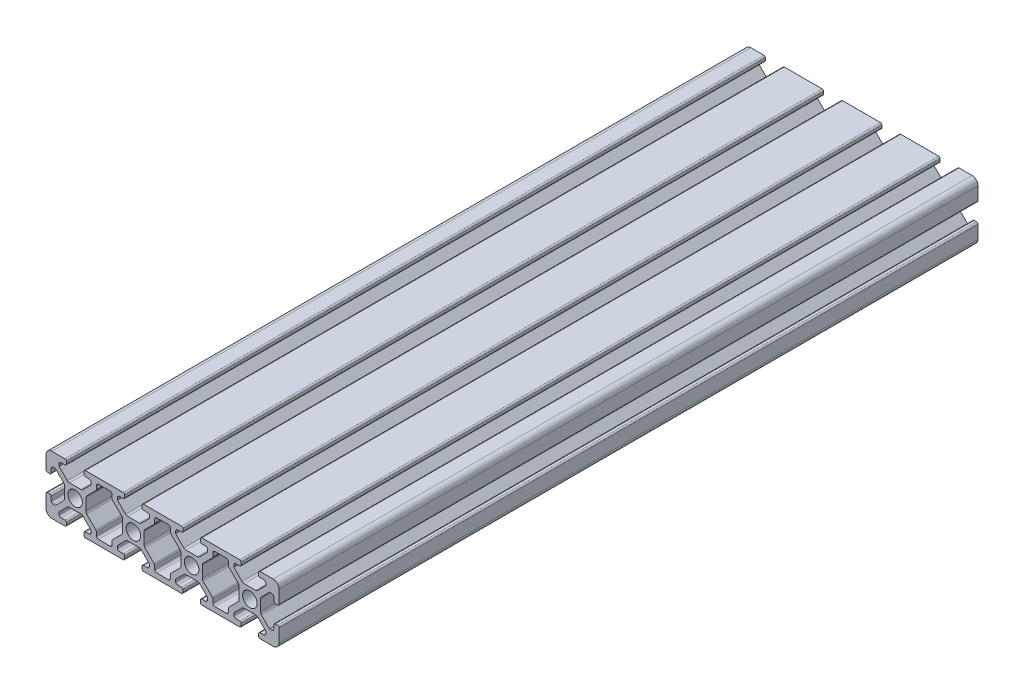
SolidWorks part; units mm, degrees
material "6063-T5"
ref_plane "Front Plane" through (0, 0, 0) normal (0, 0, 1) x (1, 0, 0)
ref_plane "Top Plane" through (0, 0, 0) normal (0, 1, 0) x (1, 0, 0)
ref_plane "Right Plane" through (0, 0, 0) normal (1, 0, 0) x (0, 0, -1)
sketch "Sketch1" plane through (0, 0, 0) normal (0, 0, 1) x (1, 0, 0)
  line L0 (2, 0) -> (6.5, 0)
  line L1 (80, 2) -> (80, 6.5)
  line L2 (78, 20) -> (73.5, 20)
  line L3 (0, 18) -> (0, 13.5)
  line L4 (33, 19.5) -> (33, 18.7)
  line L5 (27, 19.5) -> (27, 18.7)
  line L6 (7, 19.5) -> (7, 18.7)
  line L7 (13, 19.5) -> (13, 18.7)
  line L8 (6.5, 20) -> (2, 20)
  line L9 (53, 19.5) -> (53, 18.7)
  line L10 (47, 19.5) -> (47, 18.7)
  line L11 (73, 19.5) -> (73, 18.7)
  line L12 (67, 19.5) -> (67, 18.7)
  line L13 (33, 1.3) -> (33, 0.5)
  line L14 (27, 1.3) -> (27, 0.5)
  line L15 (53, 1.3) -> (53, 0.5)
  line L16 (47, 1.3) -> (47, 0.5)
  line L17 (73, 1.3) -> (73, 0.5)
  line L18 (67, 1.3) -> (67, 0.5)
  line L19 (13, 1.3) -> (13, 0.5)
  line L20 (7, 1.3) -> (7, 0.5)
  line L21 (13.5, 20) -> (26.5, 20) construction
  line L22 (26.5, 20) -> (13.5, 20)
  line L23 (46.5, 20) -> (33.5, 20)
  line L24 (66.5, 20) -> (53.5, 20)
  line L25 (73.5, 0) -> (78, 0)
  line L26 (53.5, 0) -> (66.5, 0)
  line L27 (33.5, 0) -> (46.5, 0)
  line L28 (13.5, 0) -> (26.5, 0)
  line L29 (79.5, 13) -> (78.7, 13)
  line L30 (79.5, 7) -> (78.7, 7)
  line L31 (0.5, 13) -> (1.3, 13)
  line L32 (0.5, 7) -> (1.3, 7)
  line L33 (0, 6.5) -> (0, 2)
  line L34 (80, 13.5) -> (80, 18)
  line L35 (1.8, 13.5) -> (1.8, 14.75)
  line L36 (5.25, 18.2) -> (6.5, 18.2)
  line L37 (78.2, 14.75) -> (78.2, 13.5)
  line L38 (74.75, 1.8) -> (73.5, 1.8)
  line L39 (1.8, 5.25) -> (1.8, 6.5)
  line L40 (13.5, 18.2) -> (14.75, 18.2)
  line L41 (6.5, 1.8) -> (5.25, 1.8)
  line L42 (33.5, 18.2) -> (34.75, 18.2)
  line L43 (26.5, 1.8) -> (25.25, 1.8)
  line L44 (53.5, 18.2) -> (54.75, 18.2)
  line L45 (46.5, 1.8) -> (45.25, 1.8)
  line L46 (73.5, 18.2) -> (74.75, 18.2)
  line L47 (66.5, 1.8) -> (65.25, 1.8)
  line L48 (78.2, 6.5) -> (78.2, 5.25)
  line L49 (12.6701, 13.9429) -> (15.5, 16.7728)
  line L50 (12.6701, 6.0571) -> (15.5, 3.2272)
  line L51 (32.6701, 13.9429) -> (35.5, 16.7728)
  line L52 (33.9429, 12.6701) -> (37.0803, 15.8075)
  line L53 (27.3299, 13.9429) -> (24.5, 16.7728)
  line L54 (22.9197, 15.8075) -> (26.0571, 12.6701)
  line L55 (27.3299, 6.0571) -> (24.5, 3.2272)
  line L56 (22.9197, 4.1925) -> (26.0571, 7.3299)
  line L57 (47.3299, 13.9429) -> (44.5, 16.7728)
  line L58 (42.9197, 15.8075) -> (46.0571, 12.6701)
  line L59 (47.3299, 6.0571) -> (44.5, 3.2272)
  line L60 (42.9197, 4.1925) -> (46.0571, 7.3299)
  line L61 (67.3299, 13.9429) -> (64.5, 16.7728)
  line L62 (62.9197, 15.8075) -> (66.0571, 12.6701)
  line L63 (67.3299, 6.0571) -> (64.5, 3.2272)
  line L64 (62.9197, 4.1925) -> (66.0571, 7.3299)
  line L65 (33.9429, 7.3299) -> (37.0803, 4.1925)
  line L66 (13.9429, 12.6701) -> (17.0803, 15.8075)
  line L67 (6.0571, 7.3299) -> (3.2272, 4.5)
  line L68 (7.3299, 6.0571) -> (4.5, 3.2272)
  line L69 (7.3299, 13.9429) -> (4.5, 16.7728)
  line L70 (32.6701, 6.0571) -> (35.5, 3.2272)
  line L71 (13.9429, 7.3299) -> (17.0803, 4.1925)
  line L72 (52.6701, 13.9429) -> (55.5, 16.7728)
  line L73 (6.0571, 12.6701) -> (3.2272, 15.5)
  line L74 (53.9429, 12.6701) -> (57.0803, 15.8075)
  line L75 (53.9429, 7.3299) -> (57.0803, 4.1925)
  line L76 (52.6701, 6.0571) -> (55.5, 3.2272)
  line L77 (72.6701, 13.9429) -> (75.5, 16.7728)
  line L78 (73.9429, 12.6701) -> (76.7728, 15.5)
  line L79 (73.9429, 7.3299) -> (76.7728, 4.5)
  line L80 (72.6701, 6.0571) -> (75.5, 3.2272)
  line L81 (28.037, 13.65) -> (31.963, 13.65)
  line L82 (18.05, 18.2) -> (21.95, 18.2)
  line L83 (14.75, 1.8) -> (13.5, 1.8)
  line L84 (15.5, 17.45) -> (15.5, 16.7728)
  line L85 (34.75, 1.8) -> (33.5, 1.8)
  line L86 (4.5, 17.45) -> (4.5, 16.7728)
  line L87 (54.75, 1.8) -> (53.5, 1.8)
  line L88 (24.5, 17.45) -> (24.5, 16.7728)
  line L89 (27.7144, 8.9872) -> (21.8, 3.0728) [skipped]
  line L90 (25.25, 18.2) -> (26.5, 18.2)
  line L91 (27.7144, 11.0128) -> (21.8, 16.9272) [skipped]
  line L92 (45.25, 18.2) -> (46.5, 18.2)
  line L93 (33.65, 11.963) -> (33.65, 8.037)
  line L94 (31.963, 6.35) -> (28.037, 6.35)
  line L95 (26.35, 8.037) -> (26.35, 11.963)
  line L96 (65.25, 18.2) -> (66.5, 18.2)
  line L97 (44.5, 17.45) -> (44.5, 16.7728)
  line L98 (35.5, 17.45) -> (35.5, 16.7728)
  line L99 (47.7144, 8.9872) -> (41.8, 3.0728) [skipped]
  line L100 (47.7144, 11.0128) -> (41.8, 16.9272) [skipped]
  line L101 (67.7144, 11.0128) -> (61.8, 16.9272) [skipped]
  line L102 (67.7144, 8.9872) -> (61.8, 3.0728) [skipped]
  line L103 (13.65, 11.963) -> (13.65, 8.037)
  line L104 (11.963, 6.35) -> (8.037, 6.35)
  line L105 (6.35, 8.037) -> (6.35, 11.963)
  line L106 (8.037, 13.65) -> (11.963, 13.65)
  line L107 (48.037, 13.65) -> (51.963, 13.65)
  line L108 (53.65, 11.963) -> (53.65, 8.037)
  line L109 (51.963, 6.35) -> (48.037, 6.35)
  line L110 (46.35, 8.037) -> (46.35, 11.963)
  line L111 (68.037, 13.65) -> (71.963, 13.65)
  line L112 (73.65, 11.963) -> (73.65, 8.037)
  line L113 (71.963, 6.35) -> (68.037, 6.35)
  line L114 (66.35, 8.037) -> (66.35, 11.963)
  line L115 (64.5, 17.45) -> (64.5, 16.7728)
  line L116 (55.5, 17.45) -> (55.5, 16.7728)
  line L117 (4.5, 2.55) -> (4.5, 3.2272)
  line L118 (75.5, 17.45) -> (75.5, 16.7728)
  line L119 (24.5, 2.55) -> (24.5, 3.2272)
  line L120 (15.5, 2.55) -> (15.5, 3.2272)
  line L121 (44.5, 2.55) -> (44.5, 3.2272)
  line L122 (35.5, 2.55) -> (35.5, 3.2272)
  line L123 (64.5, 2.55) -> (64.5, 3.2272)
  line L124 (55.5, 2.55) -> (55.5, 3.2272)
  line L125 (2.55, 15.5) -> (3.2272, 15.5)
  line L126 (75.5, 2.55) -> (75.5, 3.2272)
  line L127 (2.55, 4.5) -> (3.2272, 4.5)
  line L128 (77.45, 15.5) -> (76.7728, 15.5)
  line L129 (17.3, 17.45) -> (17.3, 16.3379)
  line L130 (77.45, 4.5) -> (76.7728, 4.5)
  line L131 (22.7, 17.45) -> (22.7, 16.3379)
  line L132 (38.05, 18.2) -> (41.95, 18.2)
  line L133 (37.3, 17.45) -> (37.3, 16.3379)
  line L134 (42.7, 17.45) -> (42.7, 16.3379)
  line L135 (58.05, 18.2) -> (61.95, 18.2)
  line L136 (57.3, 17.45) -> (57.3, 16.3379)
  line L137 (62.7, 17.45) -> (62.7, 16.3379)
  line L138 (17.3, 3.6621) -> (17.3, 2.55)
  line L139 (18.05, 1.8) -> (21.95, 1.8)
  line L140 (22.7, 2.55) -> (22.7, 3.6621)
  line L141 (37.3, 3.6621) -> (37.3, 2.55)
  line L142 (38.05, 1.8) -> (41.95, 1.8)
  line L143 (42.7, 2.55) -> (42.7, 3.6621)
  line L144 (57.3, 3.6621) -> (57.3, 2.55)
  line L145 (58.05, 1.8) -> (61.95, 1.8)
  line L146 (62.7, 2.55) -> (62.7, 3.6621)
  circle A0 centre (10, 10) radius 2.5
  circle A1 centre (30, 10) radius 2.5
  circle A2 centre (50, 10) radius 2.5
  circle A3 centre (70, 10) radius 2.5
  arc A4 (78, 0) -> (80, 2) centre (78, 2) ccw
  arc A5 (80, 18) -> (78, 20) centre (78, 18) ccw
  arc A6 (2, 0) -> (0, 2) centre (2, 2) cw
  arc A7 (2, 20) -> (0, 18) centre (2, 18) ccw
  arc A8 (12.6701, 13.9429) -> (11.963, 13.65) centre (11.963, 14.65) cw
  arc A9 (7.3299, 13.9429) -> (8.037, 13.65) centre (8.037, 14.65) ccw
  arc A10 (6.0571, 12.6701) -> (6.35, 11.963) centre (5.35, 11.963) cw
  arc A11 (6.0571, 7.3299) -> (6.35, 8.037) centre (5.35, 8.037) ccw
  arc A12 (7.3299, 6.0571) -> (8.037, 6.35) centre (8.037, 5.35) cw
  arc A13 (12.6701, 6.0571) -> (11.963, 6.35) centre (11.963, 5.35) ccw
  arc A14 (32.6701, 6.0571) -> (31.963, 6.35) centre (31.963, 5.35) ccw
  arc A15 (27.3299, 6.0571) -> (28.037, 6.35) centre (28.037, 5.35) cw
  arc A16 (27.3299, 13.9429) -> (28.037, 13.65) centre (28.037, 14.65) ccw
  arc A17 (32.6701, 13.9429) -> (31.963, 13.65) centre (31.963, 14.65) cw
  arc A18 (47.3299, 6.0571) -> (48.037, 6.35) centre (48.037, 5.35) cw
  arc A19 (52.6701, 6.0571) -> (51.963, 6.35) centre (51.963, 5.35) ccw
  arc A20 (52.6701, 13.9429) -> (51.963, 13.65) centre (51.963, 14.65) cw
  arc A21 (47.3299, 13.9429) -> (48.037, 13.65) centre (48.037, 14.65) ccw
  arc A22 (72.6701, 13.9429) -> (71.963, 13.65) centre (71.963, 14.65) cw
  arc A23 (67.3299, 13.9429) -> (68.037, 13.65) centre (68.037, 14.65) ccw
  arc A24 (67.3299, 6.0571) -> (68.037, 6.35) centre (68.037, 5.35) cw
  arc A25 (72.6701, 6.0571) -> (71.963, 6.35) centre (71.963, 5.35) ccw
  arc A26 (73.9429, 7.3299) -> (73.65, 8.037) centre (74.65, 8.037) cw
  arc A27 (73.9429, 12.6701) -> (73.65, 11.963) centre (74.65, 11.963) ccw
  arc A28 (66.0571, 7.3299) -> (66.35, 8.037) centre (65.35, 8.037) ccw
  arc A29 (66.0571, 12.6701) -> (66.35, 11.963) centre (65.35, 11.963) cw
  arc A30 (53.9429, 7.3299) -> (53.65, 8.037) centre (54.65, 8.037) cw
  arc A31 (53.9429, 12.6701) -> (53.65, 11.963) centre (54.65, 11.963) ccw
  arc A32 (78.2, 14.75) -> (77.45, 15.5) centre (77.45, 14.75) ccw
  arc A33 (75.5, 17.45) -> (74.75, 18.2) centre (74.75, 17.45) ccw
  arc A34 (78.2, 5.25) -> (77.45, 4.5) centre (77.45, 5.25) cw
  arc A35 (75.5, 2.55) -> (74.75, 1.8) centre (74.75, 2.55) cw
  arc A36 (46.0571, 7.3299) -> (46.35, 8.037) centre (45.35, 8.037) ccw
  arc A37 (46.0571, 12.6701) -> (46.35, 11.963) centre (45.35, 11.963) cw
  arc A38 (33.9429, 7.3299) -> (33.65, 8.037) centre (34.65, 8.037) cw
  arc A39 (33.9429, 12.6701) -> (33.65, 11.963) centre (34.65, 11.963) ccw
  arc A40 (13.9429, 12.6701) -> (13.65, 11.963) centre (14.65, 11.963) ccw
  arc A41 (13.9429, 7.3299) -> (13.65, 8.037) centre (14.65, 8.037) cw
  arc A42 (26.0571, 7.3299) -> (26.35, 8.037) centre (25.35, 8.037) ccw
  arc A43 (26.0571, 12.6701) -> (26.35, 11.963) centre (25.35, 11.963) cw
  arc A44 (65.25, 1.8) -> (64.5, 2.55) centre (65.25, 2.55) cw
  arc A45 (61.95, 1.8) -> (62.7, 2.55) centre (61.95, 2.55) ccw
  arc A46 (57.3, 2.55) -> (58.05, 1.8) centre (58.05, 2.55) ccw
  arc A47 (54.75, 1.8) -> (55.5, 2.55) centre (54.75, 2.55) ccw
  arc A48 (45.25, 1.8) -> (44.5, 2.55) centre (45.25, 2.55) cw
  arc A49 (64.5, 17.45) -> (65.25, 18.2) centre (65.25, 17.45) cw
  arc A50 (61.95, 18.2) -> (62.7, 17.45) centre (61.95, 17.45) cw
  arc A51 (58.05, 18.2) -> (57.3, 17.45) centre (58.05, 17.45) ccw
  arc A52 (53, 18.7) -> (53.5, 18.2) centre (53.5, 18.7) ccw
  arc A53 (53, 19.5) -> (53.5, 20) centre (53.5, 19.5) cw
  arc A54 (67, 18.7) -> (66.5, 18.2) centre (66.5, 18.7) cw
  arc A55 (67, 19.5) -> (66.5, 20) centre (66.5, 19.5) ccw
  arc A56 (73, 18.7) -> (73.5, 18.2) centre (73.5, 18.7) ccw
  arc A57 (73, 19.5) -> (73.5, 20) centre (73.5, 19.5) cw
  arc A58 (78.7, 13) -> (78.2, 13.5) centre (78.7, 13.5) cw
  arc A59 (79.5, 13) -> (80, 13.5) centre (79.5, 13.5) ccw
  arc A60 (78.7, 7) -> (78.2, 6.5) centre (78.7, 6.5) ccw
  arc A61 (79.5, 7) -> (80, 6.5) centre (79.5, 6.5) cw
  arc A62 (73, 0.5) -> (73.5, 0) centre (73.5, 0.5) ccw
  arc A63 (73, 1.3) -> (73.5, 1.8) centre (73.5, 1.3) cw
  arc A64 (67, 0.5) -> (66.5, 0) centre (66.5, 0.5) cw
  arc A65 (67, 1.3) -> (66.5, 1.8) centre (66.5, 1.3) ccw
  arc A66 (53, 0.5) -> (53.5, 0) centre (53.5, 0.5) ccw
  arc A67 (53, 1.3) -> (53.5, 1.8) centre (53.5, 1.3) cw
  arc A68 (47, 0.5) -> (46.5, 0) centre (46.5, 0.5) cw
  arc A69 (47, 1.3) -> (46.5, 1.8) centre (46.5, 1.3) ccw
  arc A70 (33, 0.5) -> (33.5, 0) centre (33.5, 0.5) ccw
  arc A71 (33, 1.3) -> (33.5, 1.8) centre (33.5, 1.3) cw
  arc A72 (27, 0.5) -> (26.5, 0) centre (26.5, 0.5) cw
  arc A73 (27, 1.3) -> (26.5, 1.8) centre (26.5, 1.3) ccw
  arc A74 (47, 18.7) -> (46.5, 18.2) centre (46.5, 18.7) cw
  arc A75 (47, 19.5) -> (46.5, 20) centre (46.5, 19.5) ccw
  arc A76 (33, 18.7) -> (33.5, 18.2) centre (33.5, 18.7) ccw
  arc A77 (33, 19.5) -> (33.5, 20) centre (33.5, 19.5) cw
  arc A78 (27, 18.7) -> (26.5, 18.2) centre (26.5, 18.7) cw
  arc A79 (27, 19.5) -> (26.5, 20) centre (26.5, 19.5) ccw
  arc A80 (13, 18.7) -> (13.5, 18.2) centre (13.5, 18.7) ccw
  arc A81 (13.5, 20) -> (13, 19.5) centre (13.5, 19.5) ccw
  arc A82 (13, 0.5) -> (13.5, 0) centre (13.5, 0.5) ccw
  arc A83 (13, 1.3) -> (13.5, 1.8) centre (13.5, 1.3) cw
  arc A84 (7, 0.5) -> (6.5, 0) centre (6.5, 0.5) cw
  arc A85 (7, 1.3) -> (6.5, 1.8) centre (6.5, 1.3) ccw
  arc A86 (0, 6.5) -> (0.5, 7) centre (0.5, 6.5) cw
  arc A87 (1.3, 7) -> (1.8, 6.5) centre (1.3, 6.5) cw
  arc A88 (0, 13.5) -> (0.5, 13) centre (0.5, 13.5) ccw
  arc A89 (1.3, 13) -> (1.8, 13.5) centre (1.3, 13.5) ccw
  arc A90 (6.5, 20) -> (7, 19.5) centre (6.5, 19.5) cw
  arc A91 (7, 18.7) -> (6.5, 18.2) centre (6.5, 18.7) cw
  arc A92 (55.5, 17.45) -> (54.75, 18.2) centre (54.75, 17.45) ccw
  arc A93 (44.5, 17.45) -> (45.25, 18.2) centre (45.25, 17.45) cw
  arc A94 (37.3, 2.55) -> (38.05, 1.8) centre (38.05, 2.55) ccw
  arc A95 (38.05, 18.2) -> (37.3, 17.45) centre (38.05, 17.45) ccw
  arc A96 (41.95, 18.2) -> (42.7, 17.45) centre (41.95, 17.45) cw
  arc A97 (41.95, 1.8) -> (42.7, 2.55) centre (41.95, 2.55) ccw
  arc A98 (34.75, 1.8) -> (35.5, 2.55) centre (34.75, 2.55) ccw
  arc A99 (25.25, 1.8) -> (24.5, 2.55) centre (25.25, 2.55) cw
  arc A100 (14.75, 1.8) -> (15.5, 2.55) centre (14.75, 2.55) ccw
  arc A101 (5.25, 1.8) -> (4.5, 2.55) centre (5.25, 2.55) cw
  arc A102 (2.55, 4.5) -> (1.8, 5.25) centre (2.55, 5.25) cw
  arc A103 (1.8, 14.75) -> (2.55, 15.5) centre (2.55, 14.75) cw
  arc A104 (24.5, 17.45) -> (25.25, 18.2) centre (25.25, 17.45) cw
  arc A105 (34.75, 18.2) -> (35.5, 17.45) centre (34.75, 17.45) cw
  arc A106 (21.95, 18.2) -> (22.7, 17.45) centre (21.95, 17.45) cw
  arc A107 (18.05, 18.2) -> (17.3, 17.45) centre (18.05, 17.45) ccw
  arc A108 (15.5, 17.45) -> (14.75, 18.2) centre (14.75, 17.45) ccw
  arc A109 (5.25, 18.2) -> (4.5, 17.45) centre (5.25, 17.45) ccw
  arc A110 (62.7, 3.6621) -> (62.9197, 4.1925) centre (63.45, 3.6621) cw
  arc A111 (57.3, 3.6621) -> (57.0803, 4.1925) centre (56.55, 3.6621) ccw
  arc A112 (62.7, 16.3379) -> (62.9197, 15.8075) centre (63.45, 16.3379) ccw
  arc A113 (57.3, 16.3379) -> (57.0803, 15.8075) centre (56.55, 16.3379) cw
  arc A114 (42.7, 3.6621) -> (42.9197, 4.1925) centre (43.45, 3.6621) cw
  arc A115 (37.3, 3.6621) -> (37.0803, 4.1925) centre (36.55, 3.6621) ccw
  arc A116 (42.7, 16.3379) -> (42.9197, 15.8075) centre (43.45, 16.3379) ccw
  arc A117 (37.3, 16.3379) -> (37.0803, 15.8075) centre (36.55, 16.3379) cw
  arc A118 (22.7, 16.3379) -> (22.9197, 15.8075) centre (23.45, 16.3379) ccw
  arc A119 (17.3, 16.3379) -> (17.0803, 15.8075) centre (16.55, 16.3379) cw
  arc A120 (17.3, 3.6621) -> (17.0803, 4.1925) centre (16.55, 3.6621) ccw
  arc A121 (22.7, 3.6621) -> (22.9197, 4.1925) centre (23.45, 3.6621) cw
  arc A122 (21.95, 1.8) -> (22.7, 2.55) centre (21.95, 2.55) ccw
  arc A123 (17.3, 2.55) -> (18.05, 1.8) centre (18.05, 2.55) ccw
  point P124 (0, 0)
  point P394 (17.3, 16.0272)
  dimension "D1" = 4
  dimension "D3" = 4
  dimension "D2" = 2
  dimension "D4" = 3
extrude "Boss-Extrude1" add sketch "Sketch1" along normal blind 240
